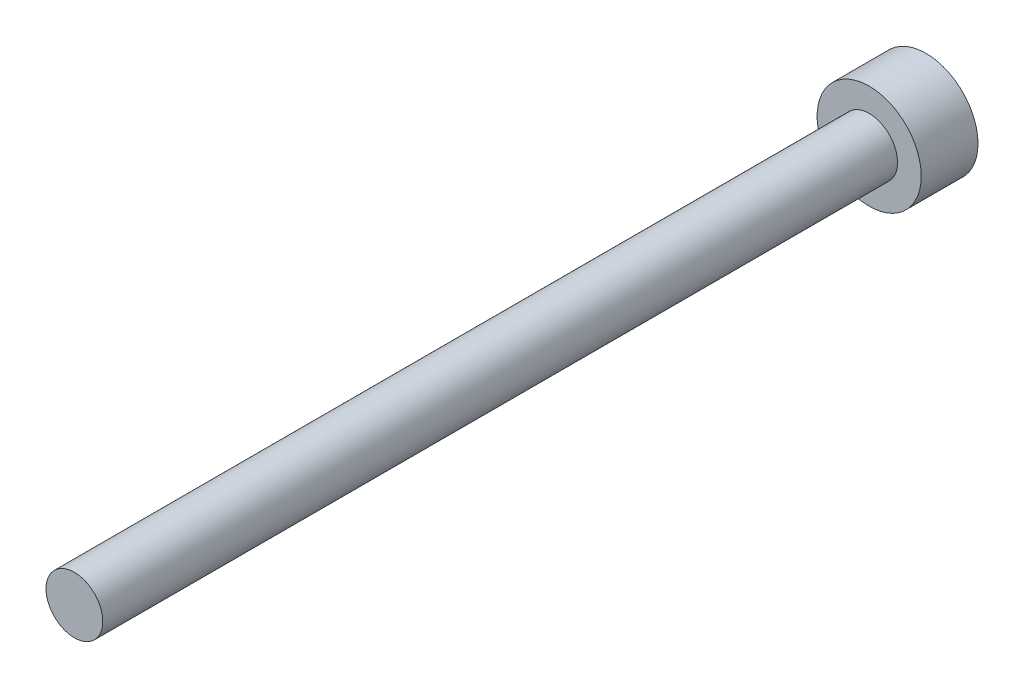
SolidWorks part; units mm, degrees
ref_plane "Front Plane" through (0, 0, 0) normal (0, 0, 1) x (1, 0, 0)
ref_plane "Top Plane" through (0, 0, 0) normal (0, 1, 0) x (1, 0, 0)
ref_plane "Right Plane" through (0, 0, 0) normal (1, 0, 0) x (0, 0, -1)
sketch "S01 - Head" plane through (0, 0, 0) normal (0, 0, 1) x (1, 0, 0)
  circle A0 centre (0, 0) radius 2.75
  dimension "D1" = 5.5
extrude "01 - Head" add sketch "S01 - Head" along normal blind 3 from offset 3
sketch "S02 - Nominal shank" plane through (0, 0, 0) normal (0, 0, 1) x (1, 0, 0)
  circle A0 centre (0, 0) radius 1.5
  dimension "D1" = 3
extrude "02 - Nominal shank" add sketch "S02 - Nominal shank" along normal blind 42
sketch "S03 - Hex key socket" plane through (0, 0, 0) normal (0, 0, 1) x (1, 0, 0)
  line L0 (1.4434, 0) -> (0.7217, 1.25)
  line L1 (0.7217, 1.25) -> (-0.7217, 1.25)
  line L2 (-0.7217, 1.25) -> (-1.4434, 0)
  line L3 (-1.4434, 0) -> (-0.7217, -1.25)
  line L4 (-0.7217, -1.25) -> (0.7217, -1.25)
  line L5 (0.7217, -1.25) -> (1.4434, 0)
  dimension "D1" = 0.7217
  dimension "D2" = 1.4434
  dimension "D3" = 0.7217
  dimension "D4" = 1.4434
  dimension "D5" = 1.25
  dimension "D6" = 1.25
extrude "03 - Hex key socket" cut sketch "S03 - Hex key socket" along normal blind 1.75 from offset 3.1
